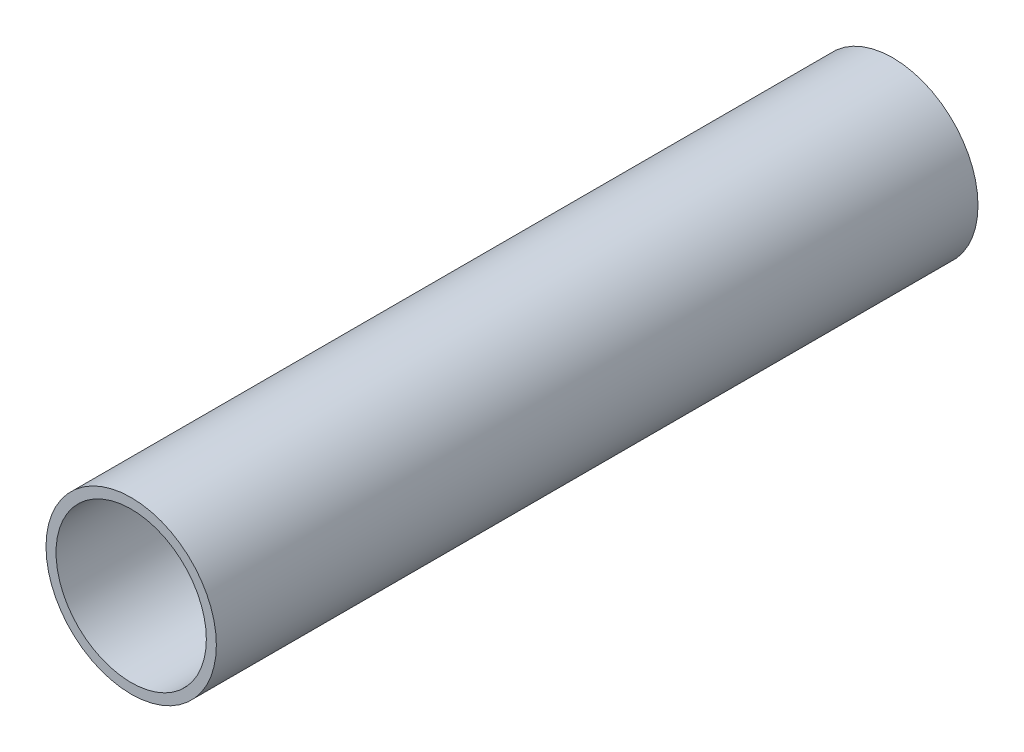
SolidWorks part; units mm, degrees
ref_plane "Plan de face" through (0, 0, 0) normal (0, 0, 1) x (1, 0, 0)
ref_plane "Plan de dessus" through (0, 0, 0) normal (0, 1, 0) x (1, 0, 0)
ref_plane "Plan de droite" through (0, 0, 0) normal (1, 0, 0) x (0, 0, -1)
sketch "Esquisse1" plane through (0, 0, 0) normal (0, 0, 1) x (1, 0, 0)
  circle A0 centre (0, 0) radius 17
  dimension "D1" = 34
extrude "Boss.-Extru.1" add sketch "Esquisse1" along normal blind 2
sketch "Esquisse2" plane through (0, 0, 2) normal (0, 0, 1) x (1, 0, 0)
  circle A0 centre (0, 0) radius 15
  circle A1 centre (0, 0) radius 17
  dimension "D1" = 30
extrude "Boss.-Extru.2" add sketch "Esquisse2" along normal blind 150
sketch "Esquisse3" plane through (0, 0, 0) normal (0, 0, -1) x (-1, 0, 0)
  circle A0 centre (0, 0) radius 12
  dimension "D1" = 24
extrude "Enlèv. mat.-Extru.1" cut sketch "Esquisse3" against normal blind 150
